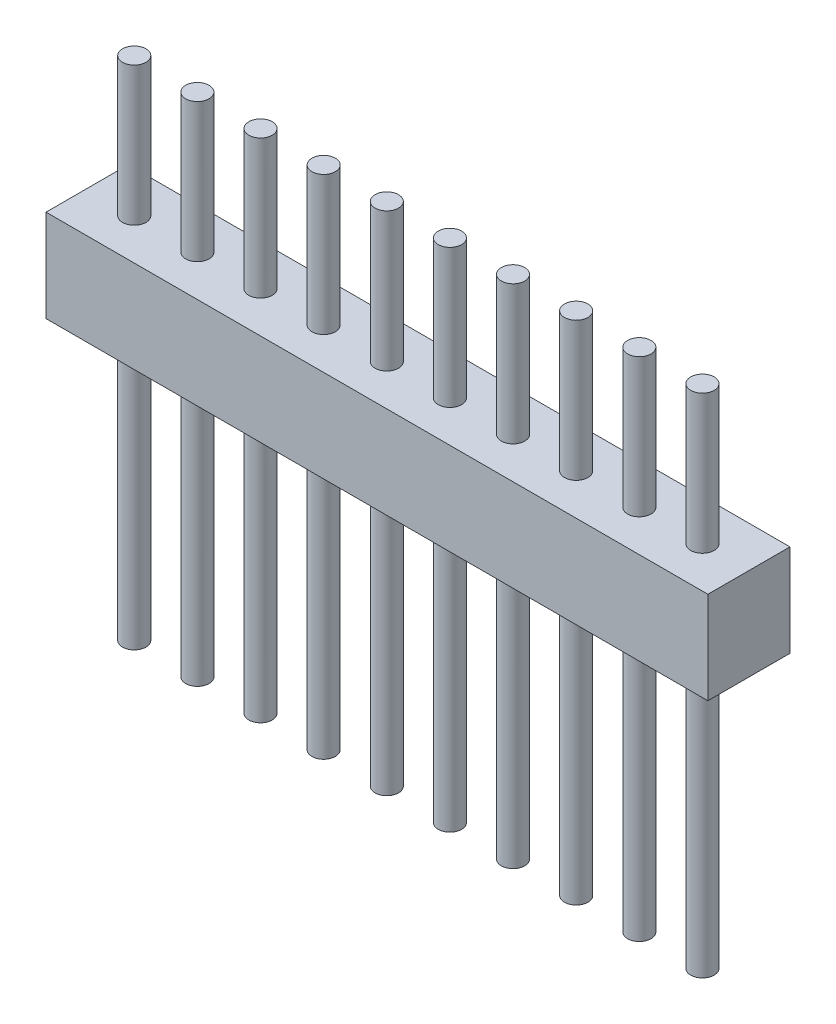
SolidWorks part; units mm, degrees
material "ABS"
ref_plane "Front Plane" through (0, 0, 0) normal (0, 0, 1) x (1, 0, 0)
ref_plane "Top Plane" through (0, 0, 0) normal (0, 1, 0) x (1, 0, 0)
ref_plane "Right Plane" through (0, 0, 0) normal (1, 0, 0) x (0, 0, -1)
sketch "Sketch1" plane through (0, 0, 0) normal (0, 1, 0) x (1, 0, 0)
  line L1 (0, 0) -> (18.66, 0)
  line L2 (0, 0) -> (0, 2.314)
  line L3 (0, 2.314) -> (18.66, 2.314)
  line L4 (18.66, 0) -> (18.66, 2.314)
  dimension "D1" = 18.66
  dimension "D2" = 2.314
extrude "Boss-Extrude1" add sketch "Sketch1" along normal blind 2.6
sketch "Sketch2" plane through (0, 2.6, 0) normal (0, 1, 0) x (1, 0, 0)
  line L0 (0, 1.157) -> (18.66, 1.157) construction
  line L1 (0, 2.314) -> (0, 0) construction
  line L2 (18.66, 0) -> (18.66, 2.314) construction
  circle A0 centre (1.33, 1.157) radius 0.33
  circle A1 centre (3.11, 1.157) radius 0.33
  circle A2 centre (4.89, 1.157) radius 0.33
  circle A3 centre (6.67, 1.157) radius 0.33
  circle A4 centre (8.45, 1.157) radius 0.33
  circle A5 centre (10.23, 1.157) radius 0.33
  circle A6 centre (12.01, 1.157) radius 0.33
  circle A7 centre (13.79, 1.157) radius 0.33
  circle A8 centre (15.57, 1.157) radius 0.33
  circle A9 centre (17.35, 1.157) radius 0.33
  dimension "D1" = 0.66
  dimension "D2" = 1.33
  dimension "D3" = 10
extrude "Boss-Extrude2" add sketch "Sketch2" along normal blind 3.91 and the other way blind 10.37
